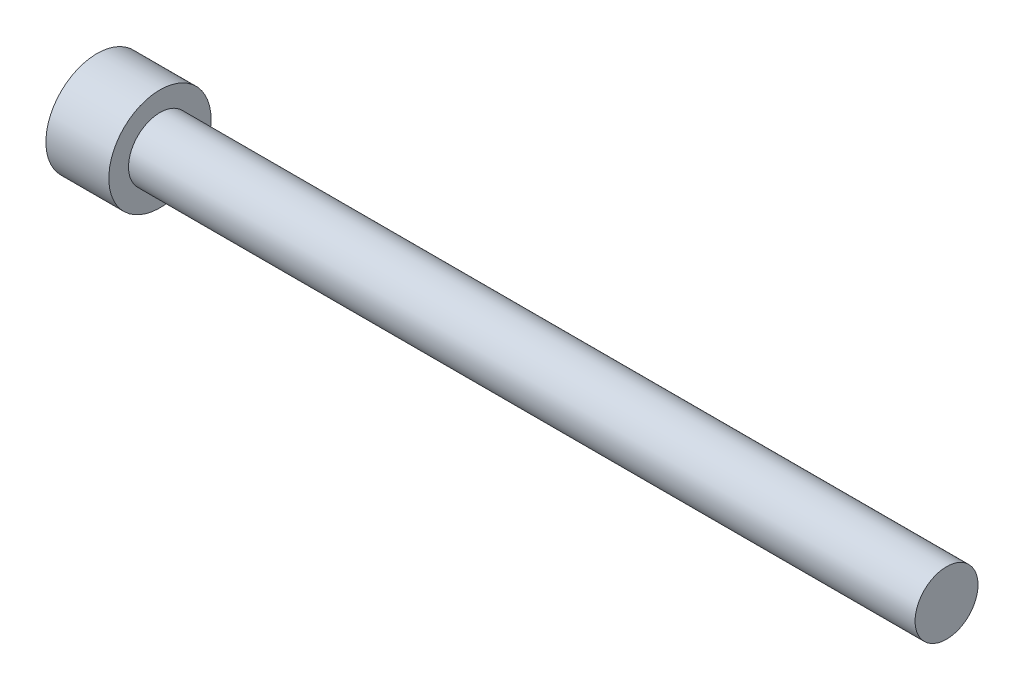
SolidWorks part; units mm, degrees
ref_plane "Front Plane" through (0, 0, 0) normal (1, 0, 0) x (0, 1, 0)
ref_plane "Top Plane" through (0, 0, 0) normal (0, 0, 1) x (0, 1, 0)
ref_plane "Right Plane" through (0, 0, 0) normal (0, 1, 0) x (-1, 0, 0)
sketch "Sketch1" plane through (0, 0, 0) normal (1, 0, 0) x (0, 1, 0)
  circle A0 centre (0, 0) radius 6.5
  dimension "D1" = 13
extrude "Boss-Extrude1" add sketch "Sketch1" along normal blind 8
sketch "Sketch2" plane through (0, 0, 0) normal (-1, 0, 0) x (0, -1, 0)
  line L1 (3.4641, 0) -> (1.7321, 3)
  line L2 (1.7321, 3) -> (-1.7321, 3)
  line L3 (-1.7321, 3) -> (-3.4641, 0)
  line L4 (-3.4641, 0) -> (-1.7321, -3)
  line L5 (-1.7321, -3) -> (1.7321, -3)
  line L6 (1.7321, -3) -> (3.4641, 0)
  circle A0 centre (0, 0) radius 3 construction
  dimension "D1" = 6
extrude "Cut-Extrude1" cut sketch "Sketch2" against normal blind 4
sketch "Sketch3" plane through (8, 0, 0) normal (1, 0, 0) x (0, 1, 0)
  circle A0 centre (0, 0) radius 4
  dimension "D1" = 8
extrude "Boss-Extrude2" add sketch "Sketch3" along normal blind 100
